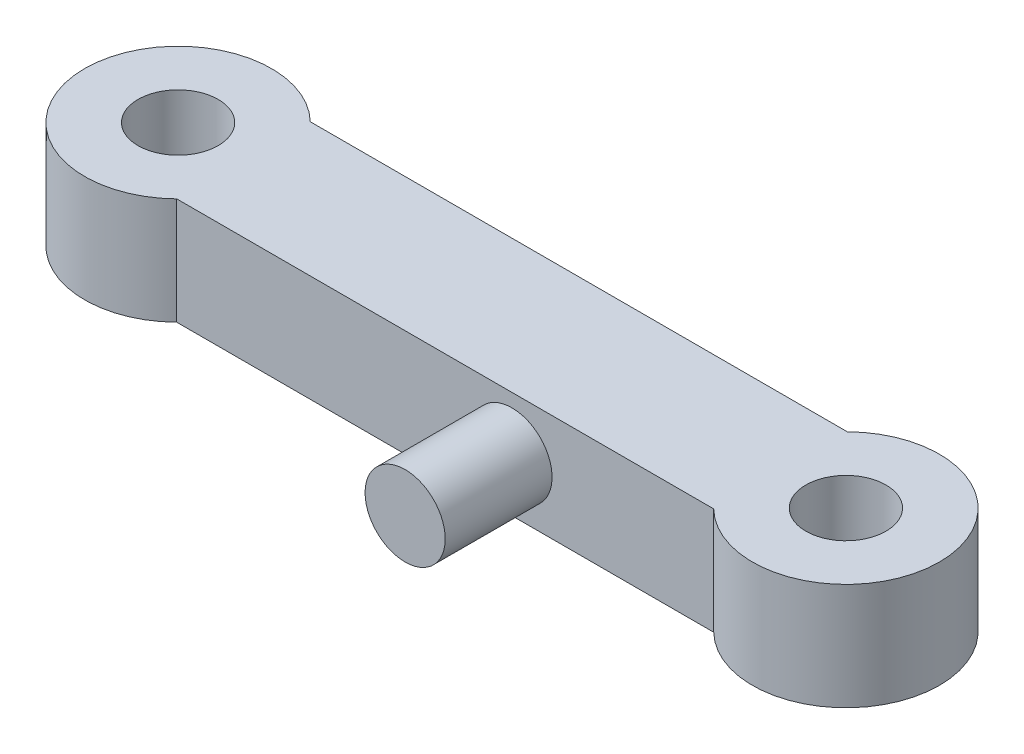
SolidWorks part; units mm, degrees
ref_plane "Спереди" through (0, 0, 0) normal (0, 0, 1) x (1, 0, 0)
ref_plane "Сверху" through (0, 0, 0) normal (0, 1, 0) x (1, 0, 0)
ref_plane "Справа" through (0, 0, 0) normal (1, 0, 0) x (0, 0, -1)
sketch "Эскиз1" plane through (0, 0, 0) normal (0, 1, 0) x (1, 0, 0)
  line L5 (-10.0505, -2.5) -> (10.0505, -2.5)
  line L7 (-10.0505, 2.5) -> (10.0505, 2.5)
  line L9 (-10.0505, -2.5) -> (10.0505, 2.5) construction
  line L10 (-10.0505, 2.5) -> (10.0505, -2.5) construction
  arc A0 (-10.0505, -2.5) -> (-10.0505, 2.5) centre (-12.5, 0) cw
  circle A1 centre (-12.5, 0) radius 1.5
  arc A2 (10.0505, 2.5) -> (10.0505, -2.5) centre (12.5, 0) cw
  circle A3 centre (12.5, 0) radius 1.5
  point P0 (0, 0)
  dimension "D1" = 3.5
  dimension "D3" = 3
  dimension "D4" = 25
  dimension "D2" = 5
extrude "Бобышка-Вытянуть1" add sketch "Эскиз1" along normal blind 4
sketch "Эскиз2" plane through (0, 0, 2.5) normal (0, 0, 1) x (1, 0, 0)
  line L1 (-989.9495, 2) -> (49010.0505, 2) construction
  line L2 (10.0505, 4) -> (10.0505, 0) construction
  circle A0 centre (2.5, 2) radius 1.5
  point P3 (5, 2)
  point P8 (10.0505, 2)
  dimension "D2" = 3
  dimension "D1" = 2.5
extrude "Бобышка-Вытянуть2" add sketch "Эскиз2" along normal blind 4
